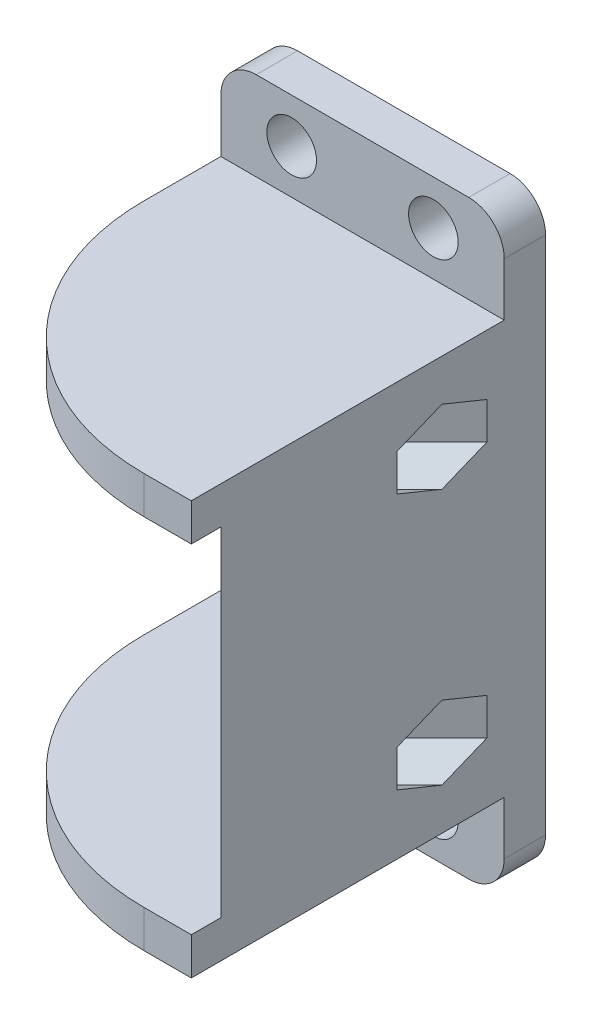
SolidWorks part; units mm, degrees
ref_plane "Front Plane" through (0, 0, 0) normal (0, 0, 1) x (1, 0, 0)
ref_plane "Top Plane" through (0, 0, 0) normal (0, 1, 0) x (1, 0, 0)
ref_plane "Right Plane" through (0, 0, 0) normal (1, 0, 0) x (0, 0, -1)
sketch "Sketch6" plane through (0, 0, 0) normal (0, 1, 0) x (1, 0, 0)
  line L1 (-12, 15) -> (12, 15)
  line L2 (-12, 15) -> (-12, -15)
  line L3 (-12, -15) -> (12, -15)
  line L4 (12, 15) -> (12, -15)
  line L5 (-12, 15) -> (12, -15) construction
  line L6 (-12, -15) -> (12, 15) construction
  point P0 (0, 0)
  dimension "D1" = 24
  dimension "D2" = 30
extrude "Boss-Extrude5" add sketch "Sketch6" along normal blind 35
ref_plane "Plane1" through (0, 17.5, 0) normal (0, 1, 0) x (1, 0, 0)
sketch "Sketch8" plane through (0, 17.5, 0) normal (0, 1, 0) x (1, 0, 0)
  line L0 (-12, 11.5) -> (-12, -15)
  line L1 (-12, 15) -> (-12, -15) construction
  line L4 (14.5, -15) -> (-12, 11.5)
  line L5 (12, 15) -> (-12, 15) construction
  line L6 (-12, -15) -> (14.5, -15)
  line L7 (-12, -15) -> (12, -15) construction
  dimension "D1" = 3.5
  dimension "D2" = 45
extrude "Cut-Extrude1" cut sketch "Sketch8" against normal offset from surface (14.325 mm away) 3.175 up to face at (0, 0, 0)
mirror "Mirror2" about plane through (0, 17.5, 0) normal (0, 1, 0) of "Cut-Extrude1"
fillet "Fillet1" radius 20 2 edges at (-12, 1.5875, 15) (-12, 33.4125, 15)
sketch "Sketch11" plane through (-0.25, 0, 0.25) normal (-0.7071, 0, 0.7071) x (0.7071, 0, 0.7071)
  line L0 (-16.617, 17.5) -> (19.5587, 17.5) construction
  line L1 (-16.617, 3.175) -> (-16.617, 31.825) construction
  circle A1 centre (4.0841, 6.65) radius 1.65
  circle A2 centre (4.0841, 28.35) radius 1.65
  dimension "D2" = 3.3
extrude "Cut-Extrude3" cut sketch "Sketch11" against normal through all
ref_plane "Plane2" through (13.8921, 0, -13.8921) normal (-0.7071, 0, 0.7071) x (0.7071, 0, 0.7071)
sketch "Sketch12" plane through (13.8921, 0, -13.8921) normal (-0.7071, 0, 0.7071) x (0.7071, 0, 0.7071)
  line L0 (13.2, 17.5) -> (-13.2, 17.5) construction
  line L1 (6.7841, 8.2088) -> (4.0841, 9.7677)
  line L2 (4.0841, 9.7677) -> (1.3841, 8.2088)
  line L3 (1.3841, 8.2088) -> (1.3841, 5.0912)
  line L4 (1.3841, 5.0912) -> (4.0841, 3.5323)
  line L5 (4.0841, 3.5323) -> (6.7841, 5.0912)
  line L6 (6.7841, 5.0912) -> (6.7841, 8.2088)
  line L7 (6.7841, 29.9088) -> (6.7841, 26.7912)
  line L8 (4.0841, 31.4677) -> (6.7841, 29.9088)
  line L9 (1.3841, 29.9088) -> (4.0841, 31.4677)
  line L10 (1.3841, 26.7912) -> (1.3841, 29.9088)
  line L11 (4.0841, 25.2323) -> (1.3841, 26.7912)
  line L12 (6.7841, 26.7912) -> (4.0841, 25.2323)
  circle A0 centre (4.0841, 6.65) radius 2.7 construction
  circle A1 centre (4.0841, 28.35) radius 2.7 construction
  dimension "D1" = 5.4
extrude "Cut-Extrude8" cut sketch "Sketch12" along normal blind 14
sketch "Sketch14" plane through (0, 0, -15) normal (0, 0, -1) x (-1, 0, 0)
  line L0 (12, 35) -> (12, 0) construction
  line L1 (12, 42.5) -> (-12, 42.5)
  line L2 (12, 42.5) -> (12, -7.5)
  line L3 (12, -7.5) -> (-12, -7.5)
  line L4 (-12, 42.5) -> (-12, -7.5)
  line L5 (-12, 35) -> (-12, 0) construction
  line L6 (13.2, 17.5) -> (-13.2, 17.5) construction
  point P8 (12, 17.5)
  dimension "D1" = 50
  dimension "D2" = 0
extrude "Boss-Extrude6" add sketch "Sketch14" against normal up to vertex (3.5 mm away)
sketch "Sketch15" plane through (0, 0, -11.5) normal (0, 0, 1) x (1, 0, 0)
  line L0 (-12, 17.5) -> (12, 17.5) construction
  line L1 (-12, 3.175) -> (-12, 31.825) construction
  line L2 (12, 31.825) -> (12, 3.175) construction
  line L4 (-12, 35) -> (-12, 42.5) construction
  line L5 (-12, 42.5) -> (12, 42.5) construction
  circle A0 centre (6, 38.75) radius 2.1
  circle A1 centre (-6, 38.75) radius 2.1
  circle A2 centre (-6, -3.75) radius 2.1
  circle A3 centre (6, -3.75) radius 2.1
  point P12 (0, 0)
  dimension "D3" = 4.2
  dimension "D1" = 12
  dimension "D2" = 6
  dimension "D4" = 3.75
extrude "Cut-Extrude9" cut sketch "Sketch15" against normal up to surface (3.5 mm away) up to face at (0, 17.5, -15)
fillet "Fillet2" radius 3 4 edges at (12, -7.5, -13.25) (-12, -7.5, -13.25) (12, 42.5, -13.25) (-12, 42.5, -13.25)
